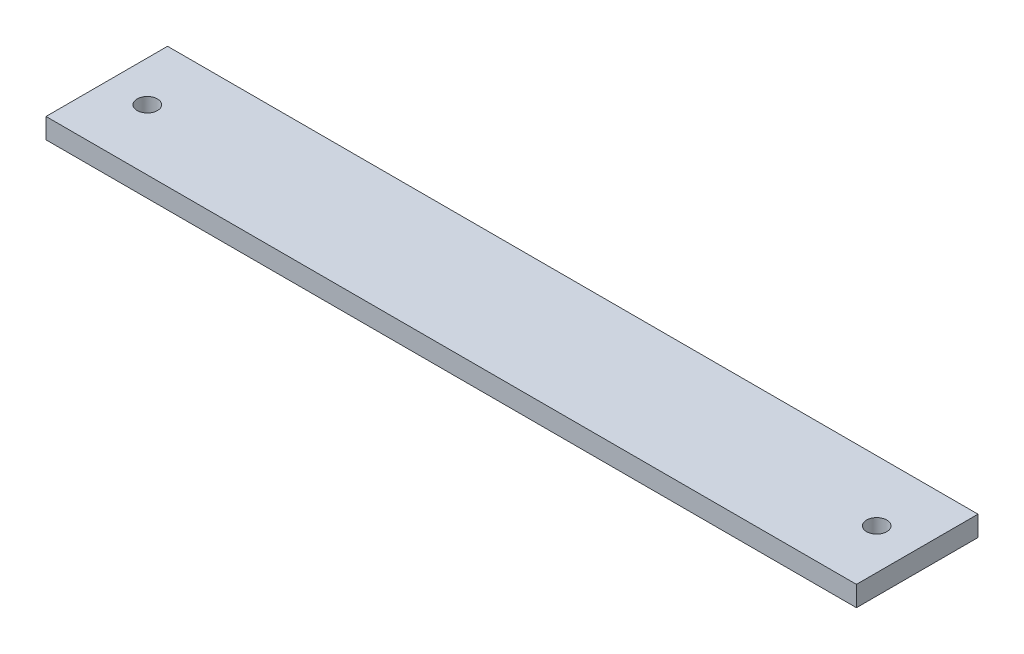
SolidWorks part; units mm, degrees
ref_plane "Front Plane" through (0, 0, 0) normal (0, 0, 1) x (1, 0, 0)
ref_plane "Top Plane" through (0, 0, 0) normal (0, 1, 0) x (1, 0, 0)
ref_plane "Right Plane" through (0, 0, 0) normal (1, 0, 0) x (0, 0, -1)
sketch "Sketch1" plane through (0, 0, 0) normal (0, 1, 0) x (1, 0, 0)
  line L0 (-14, -7.9167) -> (186, -7.9167) construction
  line L1 (-14, 7.0833) -> (186, 7.0833)
  line L2 (-14, 7.0833) -> (-14, -22.9167)
  line L3 (-14, -22.9167) -> (186, -22.9167)
  line L4 (186, 7.0833) -> (186, -22.9167)
  line L5 (86, 7.0833) -> (86, -22.9167) construction
  circle A0 centre (176, -7.9167) radius 2.5
  circle A1 centre (-4, -7.9167) radius 2.5
  dimension "D3" = 5
  dimension "D1" = 30
  dimension "D2" = 200
  dimension "D4" = 10
extrude "Boss-Extrude1" add sketch "Sketch1" along normal blind 5
